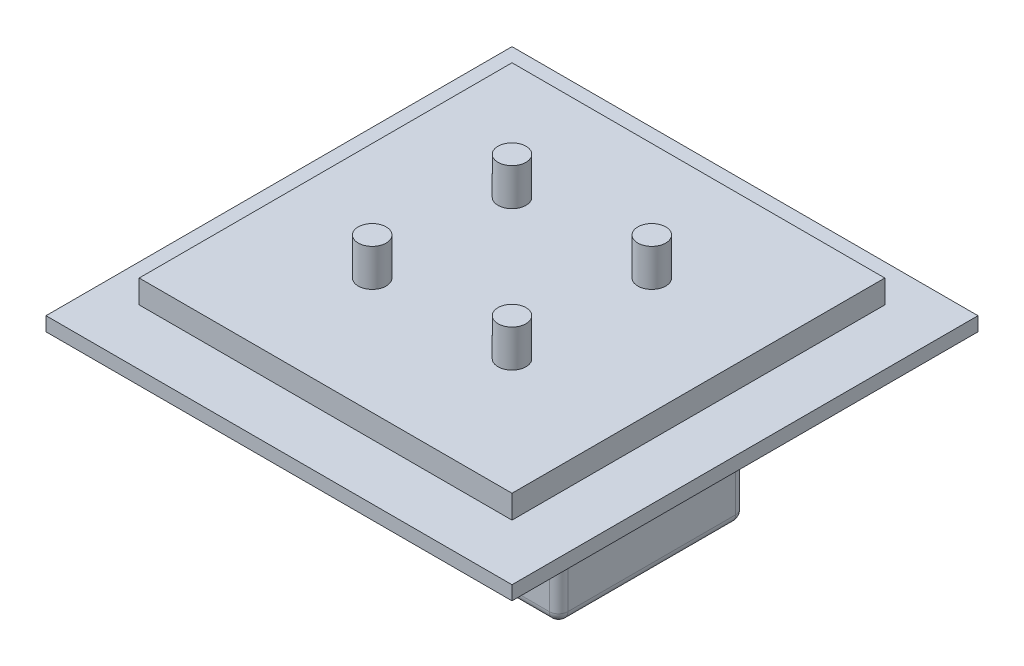
SolidWorks part; units mm, degrees
material "201 退火不锈钢 (SS)"
ref_plane "前视基准面" through (0, 0, 0) normal (0, 0, 1) x (1, 0, 0)
ref_plane "上视基准面" through (0, 0, 0) normal (0, 1, 0) x (1, 0, 0)
ref_plane "右视基准面" through (0, 0, 0) normal (1, 0, 0) x (0, 0, -1)
other "Configuration Table"
sketch "草图1" plane through (0, 0, 0) normal (0, 0, 1) x (1, 0, 0)
  line L0 (0, 0) -> (-50, 0)
  line L1 (0, 0) -> (50, 0)
  line L2 (-50, 0) -> (-50, 3)
  line L3 (-50, 3) -> (50, 3)
  line L4 (50, 3) -> (50, 0)
extrude "凸台-拉伸1" add sketch "草图1" against normal blind 100
sketch "草图2" plane through (0, 3, 0) normal (0, 1, 0) x (1, 0, 0)
  circle A0 centre (-30, 80) radius 5
  circle A1 centre (30, 80) radius 5
  circle A2 centre (-30, 20) radius 5
  circle A3 centre (30, 20) radius 5
extrude "凸台-拉伸2" add sketch "草图2" along normal blind 2
sketch "草图3" plane through (0, 5, 0) normal (0, 1, 0) x (1, 0, 0)
  line L1 (-40, 10) -> (40, 10)
  line L2 (-40, 10) -> (-40, 90)
  line L3 (-40, 90) -> (40, 90)
  line L4 (40, 10) -> (40, 90)
  line L5 (-40, 10) -> (40, 90) construction
  line L6 (-40, 90) -> (40, 10) construction
  point P0 (0, 50)
extrude "凸台-拉伸3" add sketch "草图3" along normal blind 5
sketch "草图4" plane through (0, 10, 0) normal (0, 1, 0) x (1, 0, 0)
  circle A0 centre (-15, 65) radius 3
  circle A1 centre (15, 65) radius 3
  circle A2 centre (-15, 35) radius 3
  circle A3 centre (15, 35) radius 3
extrude "凸台-拉伸4" add sketch "草图4" along normal blind 8
sketch "草图5" plane through (0, 0, 0) normal (0, -1, 0) x (1, 0, 0)
  line L1 (-30, -70) -> (30, -70)
  line L2 (-30, -70) -> (-30, -30)
  line L3 (-30, -30) -> (30, -30)
  line L4 (30, -70) -> (30, -30)
  line L5 (-30, -70) -> (30, -30) construction
  line L6 (-30, -30) -> (30, -70) construction
  point P0 (0, -50)
extrude "凸台-拉伸5" add sketch "草图5" along normal blind 30
fillet "圆角1" radius 2 8 edges at (0, -30, -70) (30, -15, -70) (30, -30, -50) (30, -15, -30) (-30, -15, -70) (-30, -30, -50) (0, -30, -30) (-30, -15, -30)
